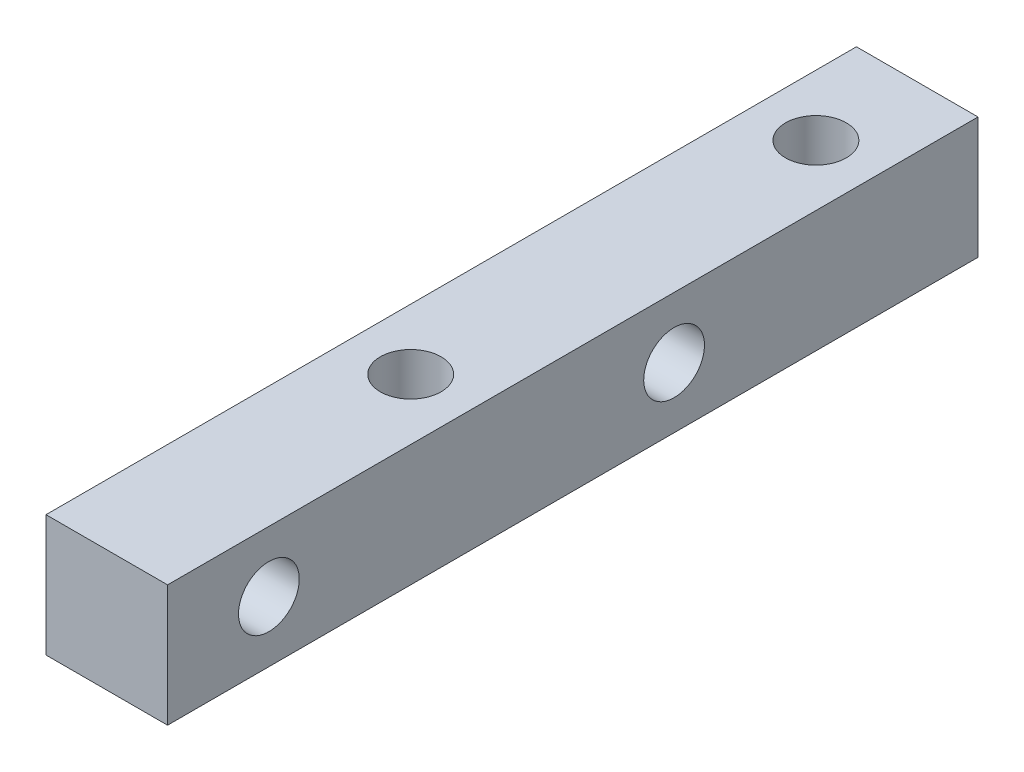
SolidWorks part; units mm, degrees
material "AISI 4130 钢，正火温度为 870C"
ref_plane "前视基准面" through (0, 0, 0) normal (0, 0, 1) x (1, 0, 0)
ref_plane "上视基准面" through (0, 0, 0) normal (0, 1, 0) x (1, 0, 0)
ref_plane "右视基准面" through (0, 0, 0) normal (1, 0, 0) x (0, 0, -1)
sketch "草图1" plane through (0, 0, 0) normal (0, 0, 1) x (1, 0, 0)
  line L1 (-3, 3) -> (3, 3)
  line L2 (-3, 3) -> (-3, -3)
  line L3 (-3, -3) -> (3, -3)
  line L4 (3, 3) -> (3, -3)
  line L5 (-3, 3) -> (3, -3) construction
  line L6 (-3, -3) -> (3, 3) construction
  point P0 (0, 0)
  dimension "D1" = 6
  dimension "D2" = 6
extrude "凸台-拉伸1" add sketch "草图1" along normal mid plane 40
sketch "草图2" plane through (3, 0, 0) normal (1, 0, 0) x (0, 0, -1)
  line L0 (-20, -3) -> (-20, 3) construction
  circle A0 centre (-15, 0) radius 1.5
  circle A1 centre (5, 0) radius 1.5
  point P7 (5, 0)
  dimension "D1" = 3
  dimension "D2" = 20
  dimension "D3" = 5
extrude "切除-拉伸1" cut sketch "草图2" against normal up to next
sketch "草图3" plane through (0, 3, 0) normal (0, 1, 0) x (1, 0, 0)
  line L0 (3, 20) -> (-3, 20) construction
  circle A0 centre (0, 15) radius 1.5
  circle A1 centre (0, -5) radius 1.5
  dimension "D1" = 20
  dimension "D2" = 5
  dimension "D3" = 3
extrude "切除-拉伸2" cut sketch "草图3" against normal up to next
